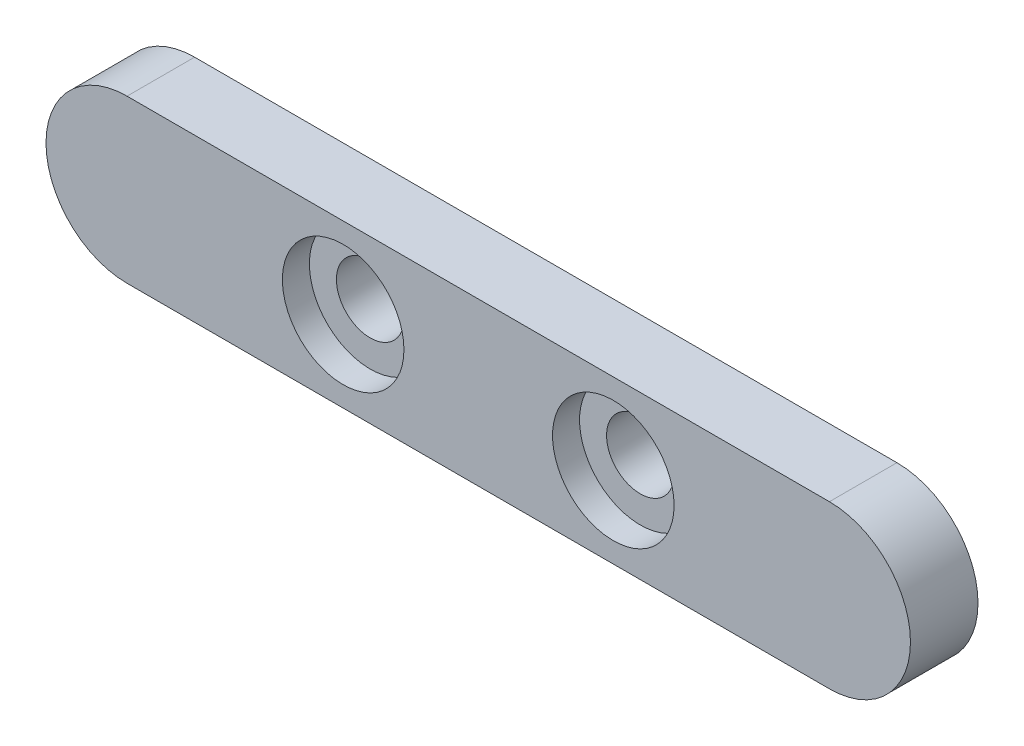
SolidWorks part; units mm, degrees
material "Vero PureWhite"
ref_plane "前视基准面" through (0, 0, 0) normal (0, 0, 1) x (1, 0, 0)
ref_plane "上视基准面" through (0, 0, 0) normal (0, 1, 0) x (1, 0, 0)
ref_plane "右视基准面" through (0, 0, 0) normal (1, 0, 0) x (0, 0, -1)
sketch "草图1" plane through (0, 0, 0) normal (0, 0, 1) x (1, 0, 0)
  line L0 (-13, 0) -> (13, 0) construction
  line L1 (-13, 3) -> (13, 3)
  line L2 (-13, -3) -> (13, -3)
  arc A0 (-13, 3) -> (-13, -3) centre (-13, 0) ccw
  arc A1 (13, -3) -> (13, 3) centre (13, 0) ccw
  circle A2 centre (5, 0) radius 1.25
  circle A3 centre (-5, 0) radius 1.25
  point P2 (0, 0)
  dimension "D1" = 3
  dimension "D5" = 2.5
  dimension "D2" = 26
  dimension "D3" = 5
  dimension "D4" = 5
extrude "凸台-拉伸1" add sketch "草图1" along normal blind 2.5
sketch "草图2" plane through (0, 0, 2.5) normal (0, 0, 1) x (1, 0, 0)
  circle A0 centre (-5, 0) radius 2.25
  circle A1 centre (5, 0) radius 2.25
  dimension "D1" = 4.5
extrude "切除-拉伸1" cut sketch "草图2" against normal blind 1
scale "缩放比例1" scale about origin uniform scaling yes scale factor 0.6
